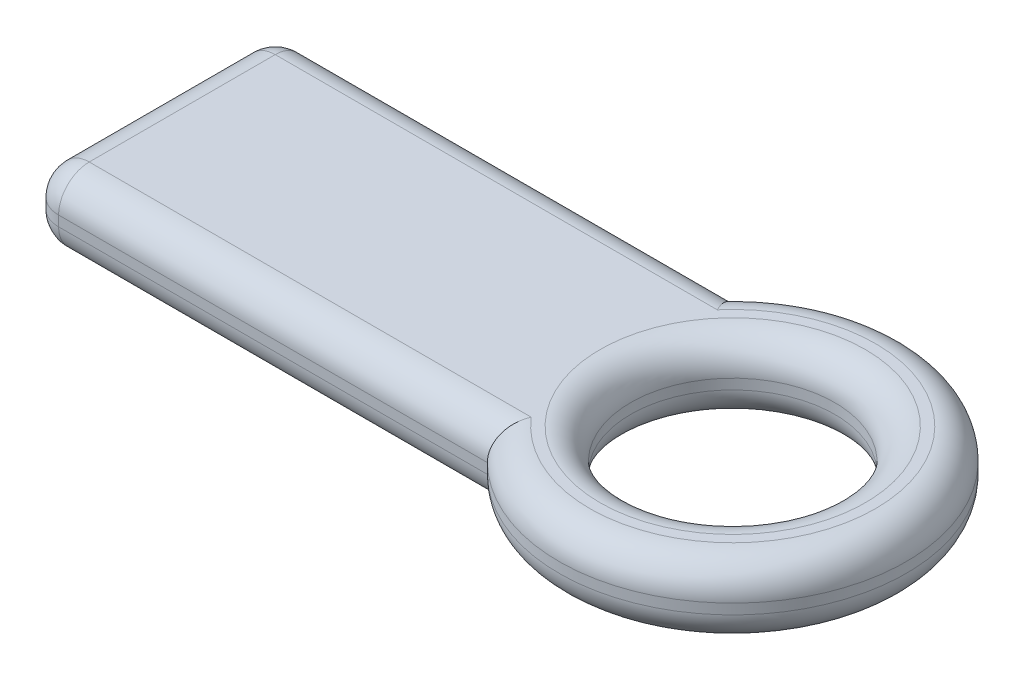
SolidWorks part; units mm, degrees
ref_plane "Front Plane" through (0, 0, 0) normal (0, 0, 1) x (1, 0, 0)
ref_plane "Top Plane" through (0, 0, 0) normal (0, 1, 0) x (1, 0, 0)
ref_plane "Right Plane" through (0, 0, 0) normal (1, 0, 0) x (0, 0, -1)
sketch "Sketch1" plane through (0, 0, 0) normal (0, 1, 0) x (1, 0, 0)
  line L1 (0, 0) -> (225.0003, 0)
  line L2 (0, 0) -> (0, 121.11)
  line L3 (0, 121.11) -> (225.0003, 121.11)
  circle A0 centre (284.65, 60.555) radius 50
  arc A1 (225.0003, 0) -> (225.0003, 121.11) centre (284.65, 60.555) ccw
  dimension "D3" = 100
  dimension "Width" = 121.11
  dimension "D5" = 60.555
  dimension "Length" = 284.65
  dimension "D4" = 35
extrude "Extrude1" add sketch "Sketch1" along normal blind 35
fillet "Fillet1" radius 15 8 edges at (112.5001, 0, -121.11) (284.65, 0, -10.555) (284.65, 35, -10.555) (369.65, 0, -60.555) (369.65, 35, -60.555) (112.5001, 35, -121.11) (112.5001, 0, 0) (112.5001, 35, 0)
fillet "Fillet2" radius 15 8 edges at (0, 17.5, -121.11) (0, 30.6066, -116.7166) (0, 4.3934, -116.7166) (0, 17.5, 0) (0, 4.3934, -4.3934) (0, 30.6066, -4.3934) (0, 0, -60.555) (0, 35, -60.555)
